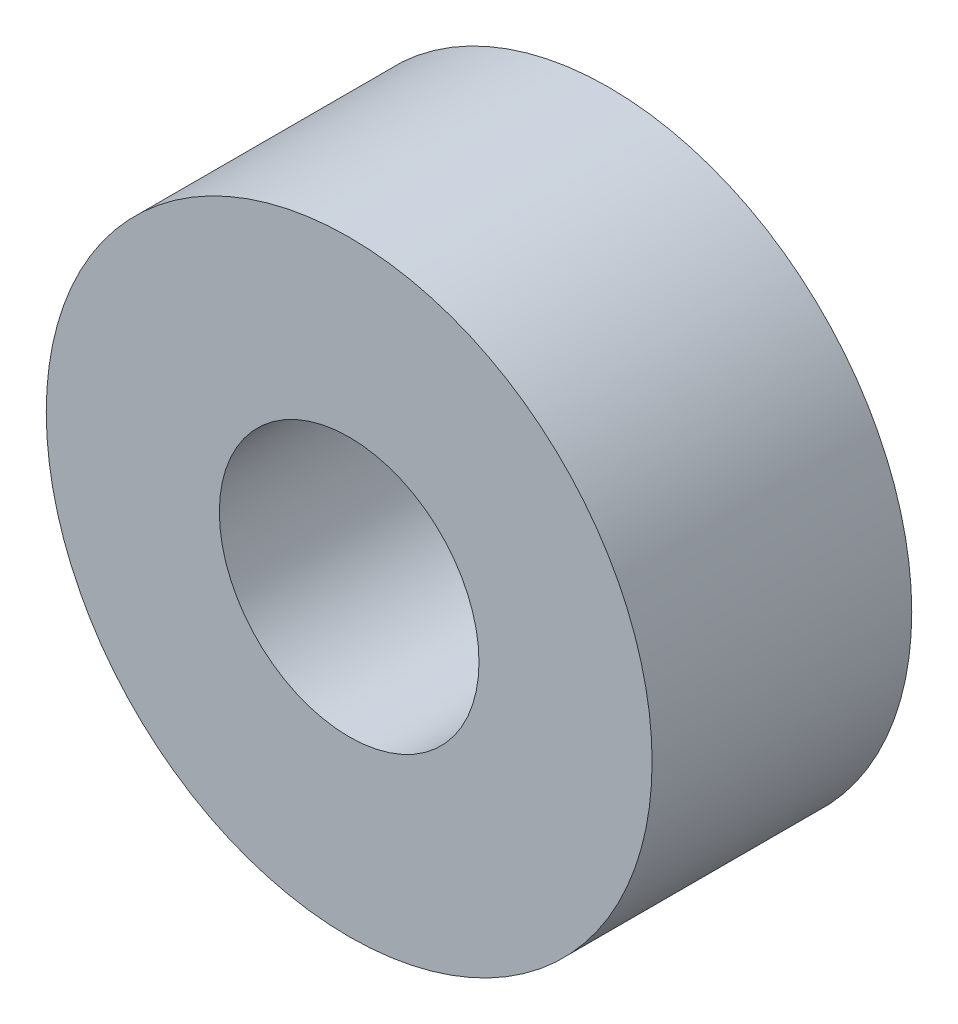
SolidWorks part; units mm, degrees
ref_plane "Piano frontale" through (0, 0, 0) normal (0, 0, 1) x (1, 0, 0)
ref_plane "Piano superiore" through (0, 0, 0) normal (0, 1, 0) x (1, 0, 0)
ref_plane "Piano destro" through (0, 0, 0) normal (1, 0, 0) x (0, 0, -1)
sketch "Schizzo1" plane through (0, 0, 0) normal (0, 0, 1) x (1, 0, 0)
  circle A0 centre (0, 0) radius 15
  circle A1 centre (0, 0) radius 35
  dimension "D1" = 30
  dimension "D2" = 70
extrude "Estrusione-Estrusione1" add sketch "Schizzo1" along normal blind 30
